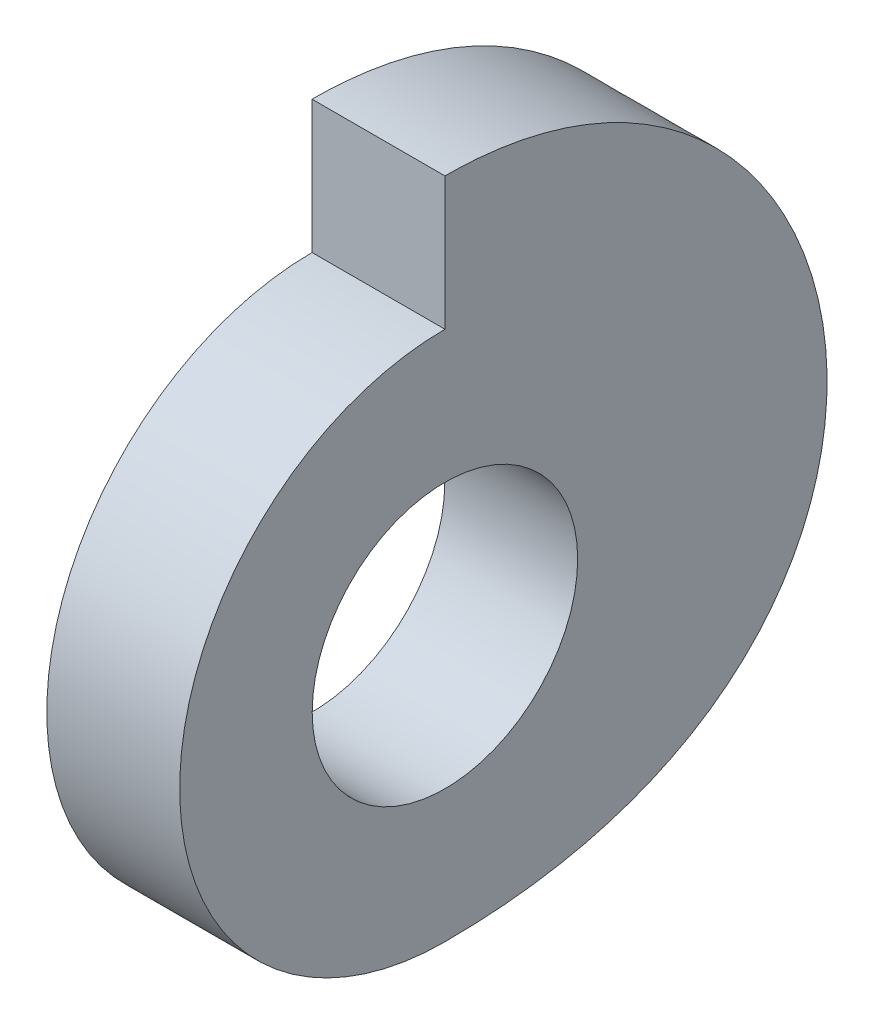
SolidWorks part; units mm, degrees
ref_plane "Front Plane" through (0, 0, 0) normal (0, 0, 1) x (1, 0, 0)
ref_plane "Top Plane" through (0, 0, 0) normal (0, 1, 0) x (1, 0, 0)
ref_plane "Right Plane" through (0, 0, 0) normal (1, 0, 0) x (0, 0, -1)
sketch "Sketch1" plane through (0, 0, 0) normal (1, 0, 0) x (0, 0, -1)
  line L0 (0, 25.3553) -> (0, 38.049)
  circle A0 centre (0, 0) radius 25.3553 construction
  circle A1 centre (0, 0) radius 38.049 construction
  arc A2 (0, 25.3553) -> (0, -25.3553) centre (0, 0) ccw
  spline S0 degree 3 poles (0, -25.3553) (55.8201, -25.3553) (41.0288, 38.049) (0, 38.049) knots 0 0 0 0 1 1 1 1
extrude "Boss-Extrude1" add sketch "Sketch1" along normal blind 12.7
sketch "Sketch2" plane through (12.7, 0, 0) normal (1, 0, 0) x (0, 0, -1)
  circle A0 centre (0, 0) radius 12.6885
extrude "Cut-Extrude1" cut sketch "Sketch2" against normal blind 12.7
